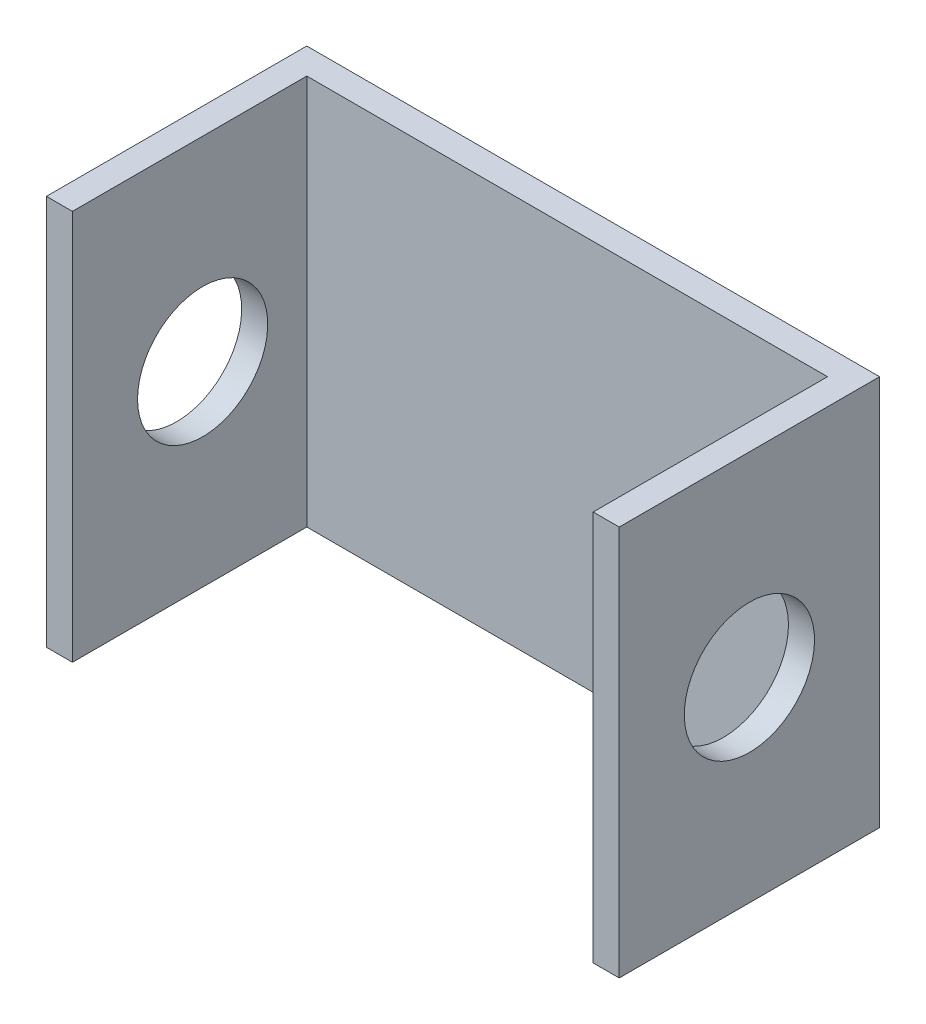
SolidWorks part; units mm, degrees
ref_plane "Front Plane" through (0, 0, 0) normal (0, 0, 1) x (1, 0, 0)
ref_plane "Top Plane" through (0, 0, 0) normal (0, 1, 0) x (1, 0, 0)
ref_plane "Right Plane" through (0, 0, 0) normal (1, 0, 0) x (0, 0, -1)
sketch "Sketch1" plane through (0, 0, 0) normal (0, 0, 1) x (1, 0, 0)
  line L1 (-41.1688, 25.3896) -> (-1.1688, 25.3896)
  line L2 (-41.1688, 25.3896) -> (-41.1688, -4.6104)
  line L3 (-41.1688, -4.6104) -> (-1.1688, -4.6104)
  line L4 (-1.1688, 25.3896) -> (-1.1688, -4.6104)
  dimension "D1" = 30
  dimension "D2" = 40
extrude "Boss-Extrude1" add sketch "Sketch1" along normal blind 2
sketch "Sketch2" plane through (-41.1688, 0, 0) normal (-1, 0, 0) x (0, 0, 1)
  line L1 (0, 25.3896) -> (20, 25.3896)
  line L2 (0, 25.3896) -> (0, -4.6104)
  line L3 (0, -4.6104) -> (20, -4.6104)
  line L4 (20, 25.3896) -> (20, -4.6104)
  dimension "D1" = 20
extrude "Boss-Extrude2" add sketch "Sketch2" along normal blind 2
sketch "Sketch3" plane through (-1.1688, 0, 0) normal (1, 0, 0) x (0, 0, -1)
  line L1 (0, 25.3896) -> (-20, 25.3896)
  line L2 (0, 25.3896) -> (0, -4.6104)
  line L3 (0, -4.6104) -> (-20, -4.6104)
  line L4 (-20, 25.3896) -> (-20, -4.6104)
extrude "Boss-Extrude3" add sketch "Sketch3" along normal blind 2
sketch "Sketch4" plane through (0.8312, 0, 0) normal (1, 0, 0) x (0, 0, -1)
  line L0 (-20, 25.3896) -> (-20, -4.6104) construction
  line L1 (0, 25.3896) -> (-20, 25.3896) construction
  circle A0 centre (-10, 10.3896) radius 5
  dimension "D1" = 10
  dimension "D2" = 10
  dimension "D3" = 15
sketch "Sketch5" plane through (0.8312, 0, 0) normal (1, 0, 0) x (0, 0, -1)
  line L0 (-20, 25.3896) -> (-20, -4.6104) construction
  line L1 (0, 25.3896) -> (-20, 25.3896) construction
  circle A0 centre (-10, 10.3896) radius 5
  dimension "D1" = 10
  dimension "D2" = 10
  dimension "D3" = 15
extrude "Cut-Extrude2" cut sketch "Sketch5" against normal through all
